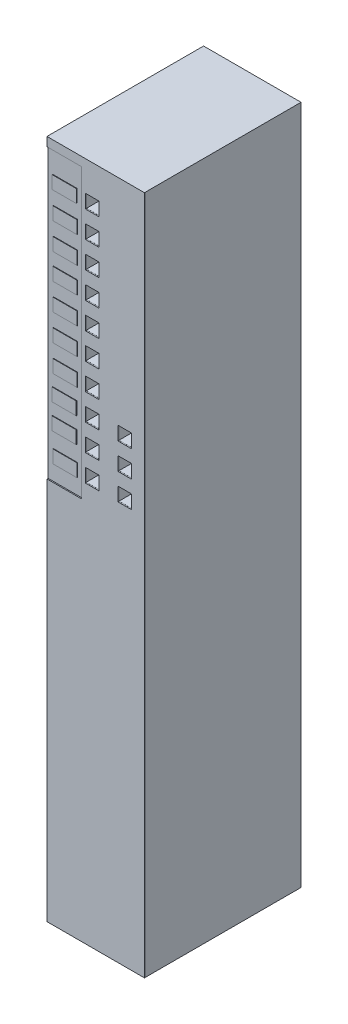
SolidWorks part; units mm, degrees
ref_plane "Alzado" through (0, 0, 0) normal (0, 0, 1) x (1, 0, 0)
ref_plane "Planta" through (0, 0, 0) normal (0, 1, 0) x (1, 0, 0)
ref_plane "Vista lateral" through (0, 0, 0) normal (1, 0, 0) x (0, 0, -1)
sketch "Croquis1" plane through (0, 0, 0) normal (0, 0, 1) x (1, 0, 0)
  line L1 (127.9371, 161.8605) -> (102.9371, 161.8605)
  line L2 (127.9371, 161.8605) -> (127.9371, 186.8605)
  line L3 (102.9371, 161.8605) -> (102.9371, 186.8605)
  line L4 (127.9371, 186.8605) -> (102.9371, 186.8605)
  line L5 (162.4902, -151.4578) -> (187.4902, -151.4578)
  line L6 (102.9371, 138.5272) -> (127.9371, 138.5272)
  line L7 (102.9371, 138.5272) -> (102.9371, 113.5272)
  line L8 (127.9371, 138.5272) -> (127.9371, 113.5272)
  line L9 (102.9371, 113.5272) -> (127.9371, 113.5272)
  line L10 (102.9371, 90.1942) -> (127.9371, 90.1942)
  line L11 (102.9371, 90.1942) -> (102.9371, 65.1942)
  line L12 (127.9371, 90.1942) -> (127.9371, 65.1942)
  line L13 (102.9371, 65.1942) -> (127.9371, 65.1942)
  line L14 (102.9371, 41.8642) -> (127.9371, 41.8642)
  line L15 (102.9371, 41.8642) -> (102.9371, 16.8642)
  line L16 (127.9371, 41.8642) -> (127.9371, 16.8642)
  line L17 (102.9371, 16.8642) -> (127.9371, 16.8642)
  line L18 (102.9371, -6.4658) -> (127.9371, -6.4658)
  line L19 (102.9371, -6.4658) -> (102.9371, -31.4658)
  line L20 (127.9371, -6.4658) -> (127.9371, -31.4658)
  line L21 (102.9371, -31.4658) -> (127.9371, -31.4658)
  line L22 (127.4902, -79.7915) -> (102.4902, -79.7915)
  line L23 (127.4902, -79.7915) -> (127.4902, -54.7915)
  line L24 (102.4902, -79.7915) -> (102.4902, -54.7915)
  line L25 (127.4902, -54.7915) -> (102.4902, -54.7915)
  line L26 (102.4902, -103.1248) -> (127.4902, -103.1248)
  line L27 (102.4902, -103.1248) -> (102.4902, -128.1248)
  line L28 (127.4902, -103.1248) -> (127.4902, -128.1248)
  line L29 (102.4902, -128.1248) -> (127.4902, -128.1248)
  line L30 (102.4902, -151.4578) -> (127.4902, -151.4578)
  line L31 (102.4902, -151.4578) -> (102.4902, -176.4578)
  line L32 (127.4902, -151.4578) -> (127.4902, -176.4578)
  line L33 (102.4902, -176.4578) -> (127.4902, -176.4578)
  line L34 (102.4902, -199.7878) -> (127.4902, -199.7878)
  line L35 (102.4902, -199.7878) -> (102.4902, -224.7878)
  line L36 (127.4902, -199.7878) -> (127.4902, -224.7878)
  line L37 (102.4902, -224.7878) -> (127.4902, -224.7878)
  line L38 (102.4902, -248.1178) -> (127.4902, -248.1178)
  line L39 (102.4902, -248.1178) -> (102.4902, -273.1178)
  line L40 (127.4902, -248.1178) -> (127.4902, -273.1178)
  line L41 (102.4902, -273.1178) -> (127.4902, -273.1178)
  line L42 (162.4902, -151.4578) -> (162.4902, -176.4578)
  line L43 (187.4902, -151.4578) -> (187.4902, -176.4578)
  line L44 (162.4902, -176.4578) -> (187.4902, -176.4578)
  line L45 (32.4902, -1004.5019) -> (211.0781, -1004.5019)
  line L46 (32.4902, -1004.5019) -> (32.4902, 241.6983)
  line L47 (162.4902, -199.7878) -> (187.4902, -199.7878)
  line L48 (162.4902, -199.7878) -> (162.4902, -224.7878)
  line L49 (187.4902, -199.7878) -> (187.4902, -224.7878)
  line L50 (162.4902, -224.7878) -> (187.4902, -224.7878)
  line L51 (162.4902, -248.1178) -> (187.4902, -248.1178)
  line L52 (162.4902, -248.1178) -> (162.4902, -273.1178)
  line L53 (187.4902, -248.1178) -> (187.4902, -273.1178)
  line L54 (162.4902, -273.1178) -> (187.4902, -273.1178)
  line L55 (211.0781, -1004.5019) -> (211.0781, 241.6983)
  line L56 (32.4902, 241.6983) -> (211.0781, 241.6983)
  point P2 (102.9371, 138.5272)
  point P7 (102.9371, 90.1942)
  point P10 (102.9371, 41.8642)
  point P15 (102.9371, -6.4658)
  point P25 (102.4902, -103.1248)
  point P31 (102.4902, -151.4578)
  point P34 (102.4902, -199.7878)
  point P39 (102.4902, -248.1178)
  point P62 (32.4902, -273.1178)
  dimension "D2" = 23.3333
  dimension "D3" = 25
  dimension "D4" = 23.333
  dimension "D5" = 25
  dimension "D6" = 25
  dimension "D7" = 23.33
  dimension "D8" = 25
  dimension "D9" = 23.33
  dimension "D10" = 25
  dimension "D11" = 23.3333
  dimension "D12" = 25
  dimension "D13" = 23.333
  dimension "D14" = 25
  dimension "D15" = 25
  dimension "D16" = 23.33
  dimension "D17" = 25
  dimension "D18" = 23.33
extrude "Saliente-Extruir2" add sketch "Croquis1" against normal blind 285
ref_plane "Plano1" through (0, 0, -285) normal (0, 0, -1) x (-1, 0, 0)
sketch "Croquis2" plane through (0, 0, -285) normal (0, 0, -1) x (-1, 0, 0)
  line L0 (-211.0781, 241.6983) -> (-32.4902, 241.6983)
  line L1 (-211.0781, 241.6983) -> (-211.0781, -309.0953)
  line L2 (-32.4902, 241.6983) -> (-32.4902, -309.0953)
  line L3 (-211.0781, -309.0953) -> (-32.4902, -309.0953)
extrude "Saliente-Extruir3" add sketch "Croquis2" against normal blind 1
ref_plane "Plano4" through (0, 0, 2) normal (0, 0, 1) x (1, 0, 0)
sketch "Croquis5" plane through (0, 0, 0) normal (0, 0, 1) x (1, 0, 0)
  line L0 (128.2238, 161.7512) -> (103.2238, 161.7512)
  line L1 (128.2238, 161.7512) -> (128.2238, 186.7512)
  line L2 (103.2238, 161.7512) -> (103.2238, 186.7512)
  line L3 (128.2238, 186.7512) -> (103.2238, 186.7512)
  line L4 (162.7769, -151.5671) -> (187.7769, -151.5671)
  line L5 (103.2238, 138.4179) -> (128.2238, 138.4179)
  line L6 (103.2238, 138.4179) -> (103.2238, 113.4179)
  line L7 (128.2238, 138.4179) -> (128.2238, 113.4179)
  line L8 (103.2238, 113.4179) -> (128.2238, 113.4179)
  line L9 (103.2238, 90.0849) -> (128.2238, 90.0849)
  line L10 (103.2238, 90.0849) -> (103.2238, 65.0849)
  line L11 (128.2238, 90.0849) -> (128.2238, 65.0849)
  line L12 (103.2238, 65.0849) -> (128.2238, 65.0849)
  line L13 (103.2238, 41.7549) -> (128.2238, 41.7549)
  line L14 (103.2238, 41.7549) -> (103.2238, 16.7549)
  line L15 (128.2238, 41.7549) -> (128.2238, 16.7549)
  line L16 (103.2238, 16.7549) -> (128.2238, 16.7549)
  line L17 (103.2238, -6.5751) -> (128.2238, -6.5751)
  line L18 (103.2238, -6.5751) -> (103.2238, -31.5751)
  line L19 (128.2238, -6.5751) -> (128.2238, -31.5751)
  line L20 (103.2238, -31.5751) -> (128.2238, -31.5751)
  line L21 (127.7769, -79.9008) -> (102.7769, -79.9008)
  line L22 (127.7769, -79.9008) -> (127.7769, -54.9008)
  line L23 (102.7769, -79.9008) -> (102.7769, -54.9008)
  line L24 (127.7769, -54.9008) -> (102.7769, -54.9008)
  line L25 (102.7769, -103.2341) -> (127.7769, -103.2341)
  line L26 (102.7769, -103.2341) -> (102.7769, -128.2341)
  line L27 (127.7769, -103.2341) -> (127.7769, -128.2341)
  line L28 (102.7769, -128.2341) -> (127.7769, -128.2341)
  line L29 (102.7769, -151.5671) -> (127.7769, -151.5671)
  line L30 (102.7769, -151.5671) -> (102.7769, -176.5671)
  line L31 (127.7769, -151.5671) -> (127.7769, -176.5671)
  line L32 (102.7769, -176.5671) -> (127.7769, -176.5671)
  line L33 (102.7769, -199.8971) -> (127.7769, -199.8971)
  line L34 (102.7769, -199.8971) -> (102.7769, -224.8971)
  line L35 (127.7769, -199.8971) -> (127.7769, -224.8971)
  line L36 (102.7769, -224.8971) -> (127.7769, -224.8971)
  line L37 (102.7769, -248.2271) -> (127.7769, -248.2271)
  line L38 (102.7769, -248.2271) -> (102.7769, -273.2271)
  line L39 (127.7769, -248.2271) -> (127.7769, -273.2271)
  line L40 (102.7769, -273.2271) -> (127.7769, -273.2271)
  line L41 (162.7769, -151.5671) -> (162.7769, -176.5671)
  line L42 (187.7769, -151.5671) -> (187.7769, -176.5671)
  line L43 (162.7769, -176.5671) -> (187.7769, -176.5671)
  line L44 (40.1339, 241.6983) -> (187.7769, 241.6983)
  line L45 (95.7914, -301.9028) -> (32.9802, -301.9028)
  line L46 (162.7769, -199.8971) -> (187.7769, -199.8971)
  line L47 (162.7769, -199.8971) -> (162.7769, -224.8971)
  line L48 (187.7769, -199.8971) -> (187.7769, -224.8971)
  line L49 (162.7769, -224.8971) -> (187.7769, -224.8971)
  line L50 (162.7769, -248.2271) -> (187.7769, -248.2271)
  line L51 (162.7769, -248.2271) -> (162.7769, -273.2271)
  line L52 (187.7769, -248.2271) -> (187.7769, -273.2271)
  line L53 (162.7769, -273.2271) -> (187.7769, -273.2271)
  line L54 (211.0781, 241.6983) -> (32.4902, 241.6983) construction
  line L55 (32.4902, -1004.5019) -> (211.0781, -1004.5019) construction
  line L56 (95.7914, 225.3423) -> (32.4902, 225.3423)
  line L57 (32.4902, 241.6983) -> (32.4902, -1004.5019) construction
  line L58 (95.7914, 225.3423) -> (95.7914, -301.9028)
  line L59 (32.4902, 225.3423) -> (32.4902, 241.6983)
  line L60 (32.4902, 241.6983) -> (40.1339, 241.6983)
  line L61 (32.9802, -301.9028) -> (32.9802, -1004.5019)
  line L62 (211.3657, -1004.5019) -> (211.3657, 241.6983)
  line L63 (211.3657, 241.6983) -> (187.7769, 241.6983)
  line L64 (32.9802, -1004.5019) -> (211.3657, -1004.5019)
  point P1 (103.2238, 138.4179)
  point P6 (103.2238, 90.0849)
  point P9 (103.2238, 41.7549)
  point P14 (103.2238, -6.5751)
  point P24 (102.7769, -103.2341)
  point P30 (102.7769, -151.5671)
  point P33 (102.7769, -199.8971)
  point P38 (102.7769, -248.2271)
  dimension "D1" = 23.3333
  dimension "D2" = 25
  dimension "D3" = 23.333
  dimension "D4" = 25
  dimension "D5" = 25
  dimension "D6" = 23.3333
  dimension "D7" = 25
  dimension "D8" = 23.333
  dimension "D9" = 25
  dimension "D10" = 25
extrude "Saliente-Extruir4" add sketch "Croquis5" along normal blind 2
ref_plane "Plano5" through (0, 0, 0) normal (0, 0, 1) x (1, 0, 0)
sketch "Croquis10" plane through (0, 0, 0) normal (0, 0, 1) x (1, 0, 0)
  line L0 (85.168, 184.788) -> (40.7729, 184.788)
  line L1 (85.168, 184.788) -> (85.168, 161.1337)
  line L2 (40.7729, 184.788) -> (40.7729, 161.1337)
  line L3 (85.168, 161.1337) -> (40.7729, 161.1337)
  line L4 (86.6248, 87.214) -> (42.2297, 87.214)
  line L5 (86.6248, 87.214) -> (86.6248, 63.5596)
  line L6 (42.2297, 87.214) -> (42.2297, 63.5596)
  line L7 (86.6248, 63.5596) -> (42.2297, 63.5596)
  line L8 (86.6248, -8.8817) -> (42.2297, -8.8817)
  line L9 (86.6248, -8.8817) -> (86.6248, -32.5361)
  line L10 (42.2297, -8.8817) -> (42.2297, -32.5361)
  line L11 (86.6248, -32.5361) -> (42.2297, -32.5361)
  line L12 (86.6248, -57.6688) -> (42.2297, -57.6688)
  line L13 (86.6248, -57.6688) -> (86.6248, -81.3231)
  line L14 (42.2297, -57.6688) -> (42.2297, -81.3231)
  line L15 (86.6248, -81.3231) -> (42.2297, -81.3231)
  line L16 (86.6248, -106.4558) -> (42.2297, -106.4558)
  line L17 (86.6248, -106.4558) -> (86.6248, -130.1101)
  line L18 (42.2297, -106.4558) -> (42.2297, -130.1101)
  line L19 (86.6248, -130.1101) -> (42.2297, -130.1101)
  line L20 (85.1464, -152.2861) -> (40.7513, -152.2861)
  line L21 (85.1464, -152.2861) -> (85.1464, -175.9404)
  line L22 (40.7513, -152.2861) -> (40.7513, -175.9404)
  line L23 (85.1464, -175.9404) -> (40.7513, -175.9404)
  line L24 (85.1464, -198.1163) -> (40.7513, -198.1163)
  line L25 (85.1464, -198.1163) -> (85.1464, -221.7706)
  line L26 (40.7513, -198.1163) -> (40.7513, -221.7706)
  line L27 (85.1464, -221.7706) -> (40.7513, -221.7706)
  line L28 (86.6248, 39.9053) -> (42.2297, 39.9053)
  line L29 (86.6248, 39.9053) -> (86.6248, 16.251)
  line L30 (42.2297, 39.9053) -> (42.2297, 16.251)
  line L31 (86.6248, 16.251) -> (42.2297, 16.251)
  line L32 (86.6248, 136.001) -> (42.2297, 136.001)
  line L33 (86.6248, 136.001) -> (86.6248, 112.3467)
  line L34 (42.2297, 136.001) -> (42.2297, 112.3467)
  line L35 (86.6248, 112.3467) -> (42.2297, 112.3467)
  line L37 (86.6248, -249.8602) -> (42.2297, -249.8602)
  line L38 (86.6248, -249.8602) -> (86.6248, -273.5145)
  line L39 (42.2297, -249.8602) -> (42.2297, -273.5145)
  line L40 (86.6248, -273.5145) -> (42.2297, -273.5145)
extrude "Saliente-Extruir5" add sketch "Croquis10" along normal blind 1
